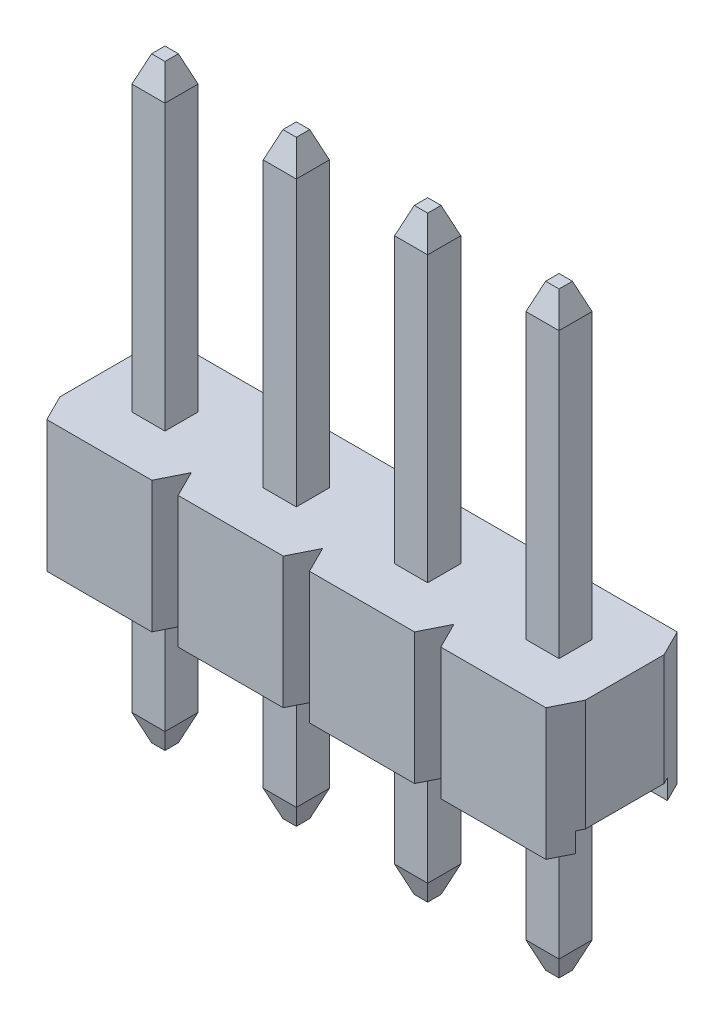
SolidWorks part; units mm, degrees
ref_plane "Front Plane" through (0, 0, 0) normal (0, 0, 1) x (1, 0, 0)
ref_plane "Top Plane" through (0, 0, 0) normal (0, 1, 0) x (1, 0, 0)
ref_plane "Right Plane" through (0, 0, 0) normal (1, 0, 0) x (0, 0, -1)
sketch "Sketch1" plane through (0, 0, 0) normal (0, 1, 0) x (1, 0, 0)
  line L1 (0, 0) -> (2.54, 0)
  line L2 (0, 0) -> (0, 2.54)
  line L3 (0, 2.54) -> (2.54, 2.54)
  line L4 (2.54, 0) -> (2.54, 2.54)
  dimension "D1" = 2.54
  dimension "D2" = 2.54
extrude "Main Body" add sketch "Sketch1" along normal blind 2.54
sketch "Sketch3" plane through (0, 0, 0) normal (-1, 0, 0) x (0, 0, 1)
  line L0 (-2.54, 0) -> (0, 0) construction
  line L1 (-2.159, 0) -> (-0.381, 0)
  line L2 (-2.159, 0) -> (-2.159, 0.381)
  line L3 (-2.159, 0.381) -> (-0.381, 0.381)
  line L4 (-0.381, 0) -> (-0.381, 0.381)
  line L5 (-2.54, 0) -> (-2.159, 0) construction
  line L6 (-0.381, 0) -> (0, 0) construction
  dimension "D1" = 0.381
extrude "Cut-Extrude1" cut sketch "Sketch3" against normal through all
sketch "Sketch4" plane through (0, 2.54, 0) normal (0, 1, 0) x (1, 0, 0)
  line L0 (0, 2.54) -> (0, 2.032)
  line L1 (0, 2.54) -> (0, 0) construction
  line L2 (0, 2.032) -> (0.254, 2.54)
  line L3 (2.54, 2.54) -> (0, 2.54) construction
  line L4 (0.254, 2.54) -> (0, 2.54)
  line L5 (2.54, 2.54) -> (2.286, 2.54)
  line L6 (2.286, 2.54) -> (2.54, 2.032)
  line L7 (2.54, 0) -> (2.54, 2.54) construction
  line L8 (2.54, 2.032) -> (2.54, 2.54)
  line L9 (2.54, 0) -> (2.286, 0)
  line L10 (0, 0) -> (2.54, 0) construction
  line L11 (2.286, 0) -> (2.54, 0.508)
  line L12 (2.54, 0.508) -> (2.54, 0)
  line L14 (0, 0) -> (0, 0.508)
  line L15 (0, 0.508) -> (0.254, 0)
  line L16 (0.254, 0) -> (0, 0)
  line M1 (0, 2.54) -> (0, 0)
  line M2 (0, 0) -> (2.54, 0)
  line M3 (2.54, 0) -> (2.54, 2.54)
  line M4 (2.54, 2.54) -> (0, 2.54)
  dimension "D1" = 0.254
  dimension "D2" = 0.508
extrude "Cut-Extrude2" cut sketch "Sketch4" against normal through all contours L2 M1 M4 | L6 M4 M3 | L15 M1 M2 | L9 L11 L12
pattern_linear "Body Pattern" count 4 spacing 2.54 along (-1, 0, 0) of "Main Body", "Cut-Extrude1", "Cut-Extrude2"
sketch "Sketch2" plane through (0, 2.54, 0) normal (0, 1, 0) x (1, 0, 0)
  line L0 (1.27, 2.54) -> (1.27, 1.59) construction
  line L1 (0.95, 0.95) -> (1.59, 0.95)
  line L2 (0.95, 0.95) -> (0.95, 1.59)
  line L3 (0.95, 1.59) -> (1.59, 1.59)
  line L4 (1.59, 0.95) -> (1.59, 1.59)
  line L6 (2.286, 2.54) -> (0.254, 2.54) construction
  line L8 (1.27, 0.95) -> (1.27, 0) construction
  line L9 (0.254, 0) -> (2.286, 0) construction
  dimension "D1" = 0.64
extrude "Pin" add sketch "Sketch2" along normal blind 6 and the other way offset from surface (5.54 mm away) 3 other way up to face at (1.27, 0, -0.1905)
chamfer "Chamfer1" distance 0.508 distance2 0.1905 4 edges at (0.95, 8.54, -1.27) (1.27, 8.54, -1.59) (1.59, 8.54, -1.27) (1.27, 8.54, -0.95)
chamfer "Chamfer2" distance 0.1905 distance2 0.508 4 edges at (1.27, -3, -1.59) (1.59, -3, -1.27) (1.27, -3, -0.95) (0.95, -3, -1.27)
pattern_linear "Pin Pattern" count 4 spacing 2.54 along (-1, 0, 0) of "Pin", "Chamfer1", "Chamfer2"
